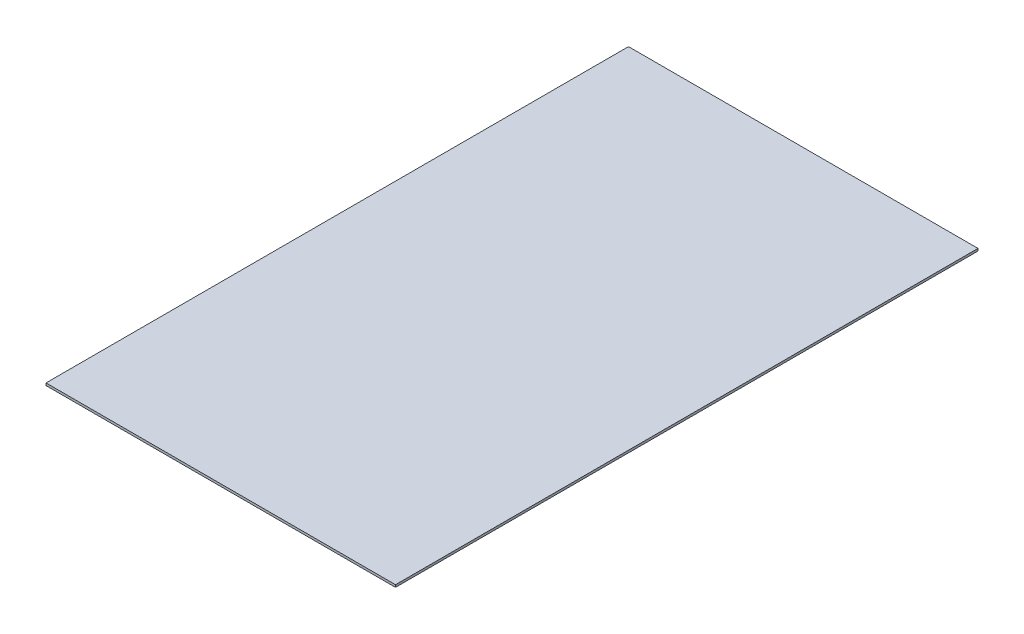
SolidWorks part; units mm, degrees
ref_plane "Front Plane" through (0, 0, 0) normal (0, 0, 1) x (1, 0, 0)
ref_plane "Top Plane" through (0, 0, 0) normal (0, 1, 0) x (1, 0, 0)
ref_plane "Right Plane" through (0, 0, 0) normal (1, 0, 0) x (0, 0, -1)
sketch "Sketch1" plane through (0, 0, 0) normal (0, 1, 0) x (1, 0, 0)
  line L1 (0, 0) -> (-30, 0)
  line L2 (0, 0) -> (0, 50)
  line L3 (0, 50) -> (-30, 50)
  line L4 (-30, 0) -> (-30, 50)
  dimension "D1" = 50
  dimension "D2" = 30
extrude "Boss-Extrude1" add sketch "Sketch1" along normal blind 0.2
